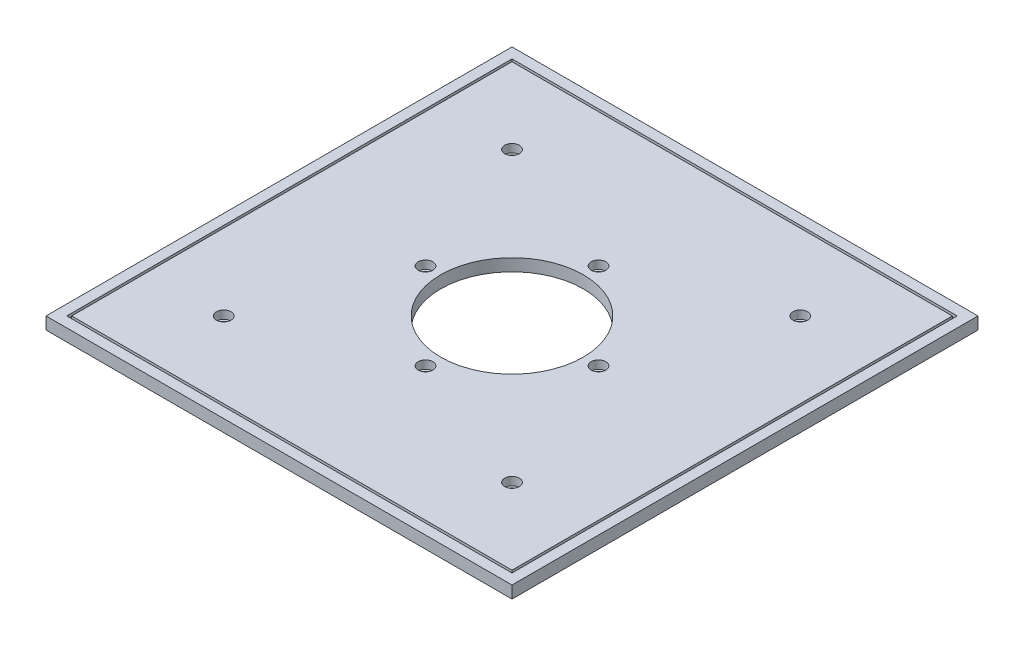
SolidWorks part; units mm, degrees
ref_plane "Front Plane" through (0, 0, 0) normal (0, 0, 1) x (1, 0, 0)
ref_plane "Top Plane" through (0, 0, 0) normal (0, 1, 0) x (1, 0, 0)
ref_plane "Right Plane" through (0, 0, 0) normal (1, 0, 0) x (0, 0, -1)
sketch "Sketch1" plane through (0, 0, 0) normal (0, 1, 0) x (1, 0, 0)
  line L0 (-285.75, -285.75) -> (-285.75, 285.75)
  line L1 (-285.75, -285.75) -> (285.75, -285.75)
  line L2 (-285.75, 285.75) -> (285.75, 285.75)
  line L3 (285.75, -285.75) -> (285.75, 285.75)
  line L4 (-285.75, -285.75) -> (285.75, 285.75) construction
  line L5 (-285.75, 285.75) -> (285.75, -285.75) construction
  point P0 (0, 0)
  point P2 (0, 0)
  dimension "D1" = 571.5
extrude "plate" add sketch "Sketch1" along normal blind 15
sketch "Sketch2" plane through (0, 15, 0) normal (0, 1, 0) x (1, 0, 0)
  circle A0 centre (0, 0) radius 87.5
  dimension "D1" = 175
extrude "bearing-hole" cut sketch "Sketch2" against normal through all
hole_wizard "CBORE for M10 SHCS" positions "Sketch5" profile "Sketch6" counterbore size "M10" standard "ANSI Metric" end condition through all
sketch "Sketch5" plane through (0, 15, 0) normal (0, 1, 0) x (1, 0, 0)
  line L1 (106.066, 0) -> (0, -106.066) construction
  line L2 (106.066, 0) -> (0, 106.066) construction
  line L3 (0, 106.066) -> (-106.066, 0) construction
  line L4 (0, -106.066) -> (-106.066, 0) construction
  line L5 (106.066, 0) -> (-106.066, 0) construction
  line L6 (0, 106.066) -> (0, -106.066) construction
  line L7 (-176.7767, 176.7767) -> (176.7767, 176.7767) construction
  line L8 (-176.7767, 176.7767) -> (-176.7767, -176.7767) construction
  line L9 (176.7767, 176.7767) -> (176.7767, -176.7767) construction
  line L10 (-176.7767, -176.7767) -> (176.7767, -176.7767) construction
  line L11 (-176.7767, 176.7767) -> (176.7767, -176.7767) construction
  line L12 (176.7767, 176.7767) -> (-176.7767, -176.7767) construction
  point P36 (0, 0)
  point P198 (-106.066, 0)
  point P201 (0, 106.066)
  point P204 (106.066, 0)
  point P207 (0, -106.066)
  point P210 (0, 0)
  point P341 (176.7767, 176.7767)
  point P344 (-176.7767, 176.7767)
  point P347 (176.7767, -176.7767)
  point P350 (-176.7767, -176.7767)
sketch "Sketch6" plane through (0, 15, 0) normal (1, 0, 0) x (0, 0, 1)
  line L0 (0, 0) -> (0, 15)
  line L1 (0, 15) -> (6, 15)
  line L2 (6, 15) -> (6, 10)
  line L3 (6, 10) -> (9, 10)
  line L4 (9, 10) -> (9, 0)
  line L5 (9, 0) -> (0, 0)
  line L6 (0, -6.35) -> (0, 107.95) construction
  dimension "Thru Hole Dia." = 12
  dimension "Thru Hole Depth" = 15
  dimension "C'Bore Dia." = 18
  dimension "C'Bore Depth" = 10
sketch "Sketch7" plane through (0, 15, 0) normal (0, 1, 0) x (1, 0, 0)
  line L1 (-273, 273) -> (273, 273)
  line L2 (-273, 273) -> (-273, -273)
  line L3 (-273, -273) -> (273, -273)
  line L4 (273, 273) -> (273, -273)
  line L5 (-273, 273) -> (273, -273) construction
  line L6 (-273, -273) -> (273, 273) construction
  line L7 (-270, 270) -> (270, 270)
  line L8 (-270, 270) -> (-270, -270)
  line L9 (-270, -270) -> (270, -270)
  line L10 (270, 270) -> (270, -270)
  line L11 (-270, 270) -> (270, -270) construction
  line L12 (-270, -270) -> (270, 270) construction
  point P0 (0, 0)
  point P6 (0, 0)
  dimension "D1" = 546
  dimension "D2" = 540
  dimension "D3" = 546
extrude "Cut-Extrude1" cut sketch "Sketch7" against normal blind 5 contours L4 L1 L2 L3 L7 L10 L9 L8
